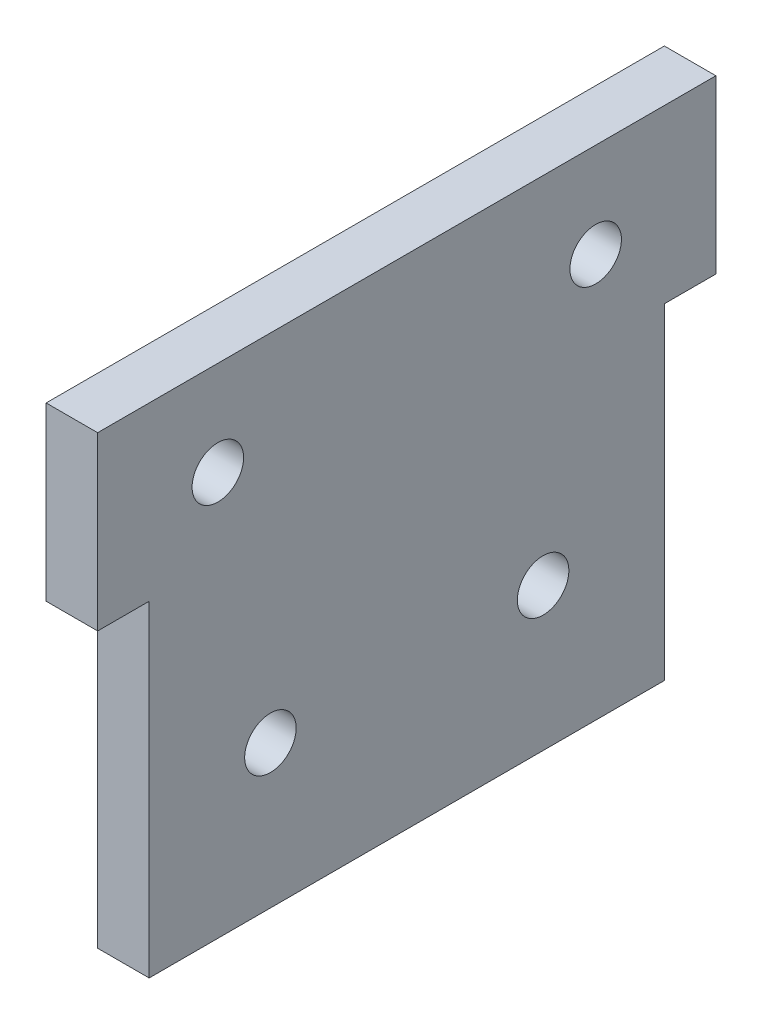
SolidWorks part; units mm, degrees
material "Acrilico TEC"
ref_plane "Front Plane" through (0, 0, 0) normal (0, 0, 1) x (1, 0, 0)
ref_plane "Top Plane" through (0, 0, 0) normal (0, 1, 0) x (1, 0, 0)
ref_plane "Right Plane" through (0, 0, 0) normal (1, 0, 0) x (0, 0, -1)
sketch "Sketch1" plane through (0, 0, 0) normal (1, 0, 0) x (0, 0, -1)
  line L0 (15, 3.2893) -> (-15, 3.2893)
  line L1 (-18, 22.2893) -> (-18, 32.2893)
  line L2 (0, 11.6193) -> (7.94, 11.6193) construction
  line L3 (-15, 3.2893) -> (-15, 22.2893)
  line L4 (18, 22.2893) -> (15, 22.2893)
  line L5 (7.94, 11.6193) -> (15, 11.6193) construction
  line L6 (15, 32.2893) -> (-15, 32.2893)
  line L7 (0, 32.2893) -> (0, 0) construction
  line L8 (-18, 22.2893) -> (-15, 22.2893)
  line L10 (-18, 32.2893) -> (-15, 32.2893)
  line L15 (15, 3.2893) -> (15, 22.2893)
  line L16 (18, 22.2893) -> (18, 32.2893)
  line L17 (18, 32.2893) -> (15, 32.2893)
  circle A0 centre (7.94, 11.6193) radius 1.5
  circle A1 centre (-7.94, 11.6193) radius 1.5
  circle A2 centre (11, 26.7893) radius 1.5
  circle A3 centre (-11, 26.7893) radius 1.5
  point P21 (0, 0)
  dimension "D6" = 3
  dimension "D7" = 3
  dimension "D1" = 19
  dimension "D2" = 3
  dimension "D3" = 7.06
  dimension "D4" = 10
  dimension "D5" = 8.33
  dimension "D8" = 11
  dimension "D9" = 5.5
extrude "Boss-Extrude1" add sketch "Sketch1" along normal blind 3
